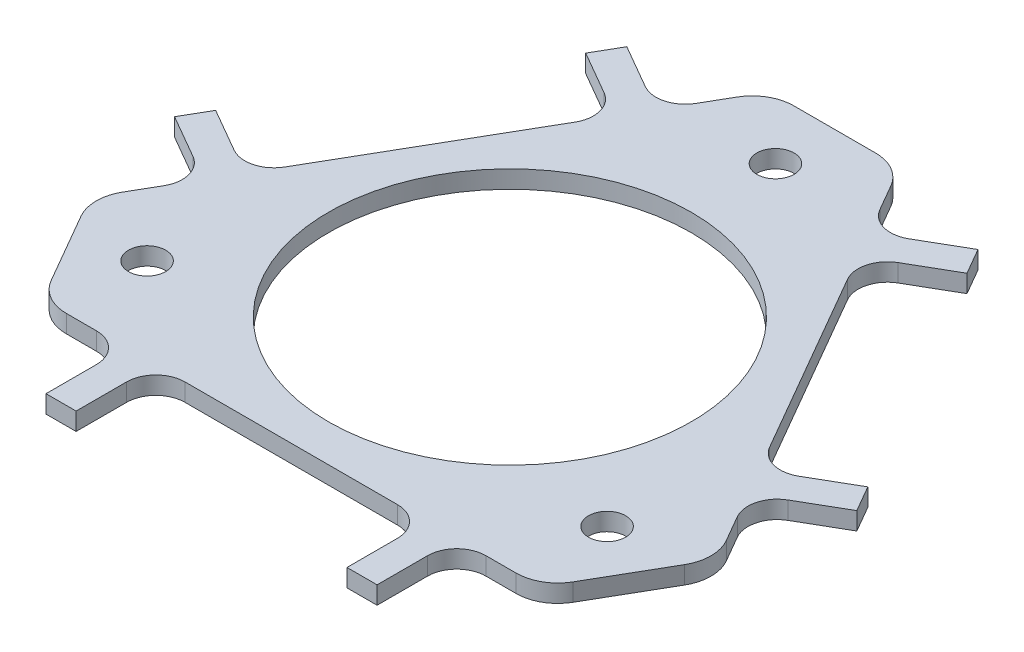
SolidWorks part; units mm, degrees
material "Thornel Mat VMA"
ref_plane "Front Plane" through (0, 0, 0) normal (0, 0, 1) x (1, 0, 0)
ref_plane "Top Plane" through (0, 0, 0) normal (0, 1, 0) x (1, 0, 0)
ref_plane "Right Plane" through (0, 0, 0) normal (1, 0, 0) x (0, 0, -1)
sketch "Sketch1" plane through (0, 0, 0) normal (0, 1, 0) x (1, 0, 0)
  line L0 (49.1829, 65.2758) -> (47.4812, 68.2233) construction
  line L1 (58.5771, 67.0046) -> (53.5542, 64.1046) construction
  line L2 (60.3771, 63.8869) -> (58.5771, 67.0046) construction
  line L3 (55.3542, 60.9869) -> (60.3771, 63.8869) construction
  line L4 (66.1829, 35.831) -> (54.1829, 56.6156) construction
  line L5 (75.5771, 37.5597) -> (70.5542, 34.6597) construction
  line L6 (77.3771, 34.442) -> (75.5771, 37.5597) construction
  line L7 (72.3542, 31.542) -> (77.3771, 34.442) construction
  line L8 (72.8846, 24.2233) -> (71.1829, 27.1707) construction
  line L9 (68.2658, 11.4233) -> (72.8846, 19.4233) construction
  line L10 (60.7055, 9.0233) -> (64.1089, 9.0233) construction
  line L11 (57.5055, 0.0233) -> (57.5055, 5.8233) construction
  line L12 (53.9055, 0.0233) -> (57.5055, 0.0233) construction
  line L13 (53.9055, 5.8233) -> (53.9055, 0.0233) construction
  line L14 (26.7055, 9.0233) -> (50.7055, 9.0233) construction
  line L15 (23.5055, 0.0233) -> (23.5055, 5.8233) construction
  line L16 (19.9055, 0.0233) -> (23.5055, 0.0233) construction
  line L17 (19.9055, 5.8233) -> (19.9055, 0.0233) construction
  line L18 (13.3021, 9.0233) -> (16.7055, 9.0233) construction
  line L19 (4.5263, 19.4233) -> (9.1451, 11.4233) construction
  line L20 (6.228, 27.1707) -> (4.5263, 24.2233) construction
  line L21 (0.0338, 34.442) -> (5.0568, 31.542) construction
  line L22 (1.8338, 37.5597) -> (0.0338, 34.442) construction
  line L23 (6.8568, 34.6597) -> (1.8338, 37.5597) construction
  line L24 (23.228, 56.6156) -> (11.228, 35.831) construction
  line L25 (17.0338, 63.8869) -> (22.0568, 60.9869) construction
  line L26 (18.8338, 67.0046) -> (17.0338, 63.8869) construction
  line L27 (23.8568, 64.1046) -> (18.8338, 67.0046) construction
  line L28 (29.9297, 68.2233) -> (28.228, 65.2758) construction
  line L29 (43.3243, 70.6233) -> (34.0867, 70.6233) construction
  line L30 (0, 0) -> (57.962, 0) construction
  line L31 (0, 0) -> (0, 59.8321) construction
  line L32 (49.0963, 65.2258) -> (47.3946, 68.1733)
  line L33 (43.3243, 70.5233) -> (34.0867, 70.5233)
  line L34 (30.0163, 68.1733) -> (28.3146, 65.2258)
  line L35 (23.8068, 64.018) -> (18.8704, 66.868)
  line L36 (18.8704, 66.868) -> (17.1704, 63.9235)
  line L37 (17.1704, 63.9235) -> (22.1068, 61.0735)
  line L38 (23.3146, 56.5656) -> (11.3146, 35.781)
  line L39 (6.8068, 34.5731) -> (1.8704, 37.4231)
  line L40 (1.8704, 37.4231) -> (0.1704, 34.4786)
  line L41 (0.1704, 34.4786) -> (5.1068, 31.6286)
  line L42 (6.3146, 27.1207) -> (4.6129, 24.1733)
  line L43 (4.6129, 19.4733) -> (9.2317, 11.4733)
  line L44 (13.3021, 9.1233) -> (16.7055, 9.1233)
  line L45 (20.0055, 5.8233) -> (20.0055, 0.1233)
  line L46 (20.0055, 0.1233) -> (23.4055, 0.1233)
  line L47 (23.4055, 0.1233) -> (23.4055, 5.8233)
  line L48 (26.7055, 9.1233) -> (50.7055, 9.1233)
  line L49 (54.0055, 5.8233) -> (54.0055, 0.1233)
  line L50 (54.0055, 0.1233) -> (57.4055, 0.1233)
  line L51 (57.4055, 0.1233) -> (57.4055, 5.8233)
  line L52 (60.7055, 9.1233) -> (64.1089, 9.1233)
  line L53 (68.1792, 11.4733) -> (72.798, 19.4733)
  line L54 (72.798, 24.1733) -> (71.0963, 27.1207)
  line L55 (72.3042, 31.6286) -> (77.2405, 34.4786)
  line L56 (77.2405, 34.4786) -> (75.5405, 37.4231)
  line L57 (75.5405, 37.4231) -> (70.6042, 34.5731)
  line L58 (66.0963, 35.781) -> (54.0963, 56.5656)
  line L59 (55.3042, 61.0735) -> (60.2405, 63.9235)
  line L60 (60.2405, 63.9235) -> (58.5405, 66.868)
  line L61 (58.5405, 66.868) -> (53.6042, 64.018)
  arc A0 (47.4812, 68.2233) -> (43.3243, 70.6233) centre (43.3243, 65.8233) ccw construction
  arc A1 (49.1829, 65.2758) -> (53.5542, 64.1046) centre (51.9542, 66.8758) ccw construction
  arc A2 (55.3542, 60.9869) -> (54.1829, 56.6156) centre (56.9542, 58.2156) ccw construction
  arc A3 (66.1829, 35.831) -> (70.5542, 34.6597) centre (68.9542, 37.431) ccw construction
  arc A4 (72.3542, 31.542) -> (71.1829, 27.1707) centre (73.9542, 28.7707) ccw construction
  arc A5 (72.8846, 19.4233) -> (72.8846, 24.2233) centre (68.7277, 21.8233) ccw construction
  arc A6 (64.1089, 9.0233) -> (68.2658, 11.4233) centre (64.1089, 13.8233) ccw construction
  arc A7 (60.7055, 9.0233) -> (57.5055, 5.8233) centre (60.7055, 5.8233) ccw construction
  arc A8 (53.9055, 5.8233) -> (50.7055, 9.0233) centre (50.7055, 5.8233) ccw construction
  arc A9 (26.7055, 9.0233) -> (23.5055, 5.8233) centre (26.7055, 5.8233) ccw construction
  arc A10 (19.9055, 5.8233) -> (16.7055, 9.0233) centre (16.7055, 5.8233) ccw construction
  arc A11 (9.1451, 11.4233) -> (13.3021, 9.0233) centre (13.3021, 13.8233) ccw construction
  arc A12 (4.5263, 24.2233) -> (4.5263, 19.4233) centre (8.6833, 21.8233) ccw construction
  arc A13 (6.228, 27.1707) -> (5.0568, 31.542) centre (3.4568, 28.7707) ccw construction
  arc A14 (6.8568, 34.6597) -> (11.228, 35.831) centre (8.4568, 37.431) ccw construction
  arc A15 (23.228, 56.6156) -> (22.0568, 60.9869) centre (20.4568, 58.2156) ccw construction
  arc A16 (23.8568, 64.1046) -> (28.228, 65.2758) centre (25.4568, 66.8758) ccw construction
  arc A17 (34.0867, 70.6233) -> (29.9297, 68.2233) centre (34.0867, 65.8233) ccw construction
  arc A18 (47.3946, 68.1733) -> (43.3243, 70.5233) centre (43.3243, 65.8233) ccw
  arc A19 (34.0867, 70.5233) -> (30.0163, 68.1733) centre (34.0867, 65.8233) ccw
  arc A20 (23.8068, 64.018) -> (28.3146, 65.2258) centre (25.4568, 66.8758) ccw
  arc A21 (23.3146, 56.5656) -> (22.1068, 61.0735) centre (20.4568, 58.2156) ccw
  arc A22 (6.8068, 34.5731) -> (11.3146, 35.781) centre (8.4568, 37.431) ccw
  arc A23 (6.3146, 27.1207) -> (5.1068, 31.6286) centre (3.4568, 28.7707) ccw
  arc A24 (4.6129, 24.1733) -> (4.6129, 19.4733) centre (8.6833, 21.8233) ccw
  arc A25 (9.2317, 11.4733) -> (13.3021, 9.1233) centre (13.3021, 13.8233) ccw
  arc A26 (20.0055, 5.8233) -> (16.7055, 9.1233) centre (16.7055, 5.8233) ccw
  arc A27 (26.7055, 9.1233) -> (23.4055, 5.8233) centre (26.7055, 5.8233) ccw
  arc A28 (54.0055, 5.8233) -> (50.7055, 9.1233) centre (50.7055, 5.8233) ccw
  arc A29 (60.7055, 9.1233) -> (57.4055, 5.8233) centre (60.7055, 5.8233) ccw
  arc A30 (64.1089, 9.1233) -> (68.1792, 11.4733) centre (64.1089, 13.8233) ccw
  arc A31 (72.798, 19.4733) -> (72.798, 24.1733) centre (68.7277, 21.8233) ccw
  arc A32 (72.3042, 31.6286) -> (71.0963, 27.1207) centre (73.9542, 28.7707) ccw
  arc A33 (66.0963, 35.781) -> (70.6042, 34.5731) centre (68.9542, 37.431) ccw
  arc A34 (55.3042, 61.0735) -> (54.0963, 56.5656) centre (56.9542, 58.2156) ccw
  arc A35 (49.0963, 65.2258) -> (53.6042, 64.018) centre (51.9542, 66.8758) ccw
  dimension "D1" = 0.1
extrude "Boss-Extrude1" add sketch "Sketch1" along normal blind 2
sketch "Sketch3" plane through (0, 2, 0) normal (0, 1, 0) x (1, 0, 0)
  line L0 (17.3146, 46.1733) -> (38.7055, 33.8233) construction
  line L1 (23.3146, 56.5656) -> (11.3146, 35.781) construction
  line L2 (38.7055, 9.1233) -> (38.7055, 33.8233) construction
  line L4 (26.7055, 9.1233) -> (50.7055, 9.1233) construction
  line L5 (60.0963, 46.1733) -> (38.7055, 33.8233) construction
  line L6 (66.0963, 35.781) -> (54.0963, 56.5656) construction
sketch "Sketch4" plane through (0, 2, 0) normal (0, 1, 0) x (1, 0, 0)
  line L0 (38.7055, 33.8233) -> (38.7055, 63.8233) construction
  line L1 (38.7055, 33.8233) -> (12.7247, 18.8233) construction
  line L2 (38.7055, 33.8233) -> (64.6862, 18.8233) construction
  circle A0 centre (38.7055, 33.8233) radius 30 construction
  circle A1 centre (38.7055, 63.8233) radius 2.1
  circle A2 centre (12.7247, 18.8233) radius 2.1
  circle A3 centre (64.6862, 18.8233) radius 2.1
  dimension "D1" = 60
  dimension "D4" = 4.2
  dimension "D2" = 120
  dimension "D3" = 120
extrude "Cut-Extrude1" cut sketch "Sketch4" against normal through all
sketch "Sketch5" plane through (0, 2, 0) normal (0, 1, 0) x (1, 0, 0)
  circle A0 centre (38.7055, 33.8233) radius 20.5
  dimension "D1" = 41
extrude "Cut-Extrude2" cut sketch "Sketch5" against normal through all
